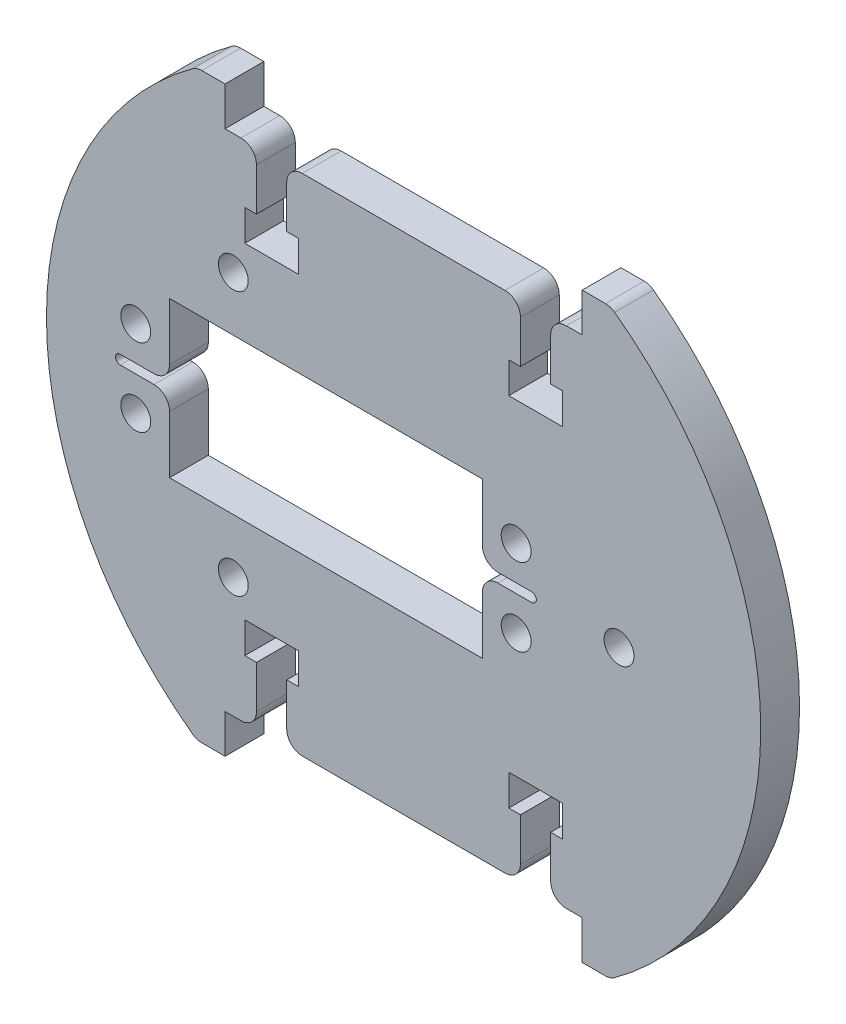
SolidWorks part; units mm, degrees
ref_plane "Plan de face" through (0, 0, 0) normal (0, 0, 1) x (1, 0, 0)
ref_plane "Plan de dessus" through (0, 0, 0) normal (0, 1, 0) x (1, 0, 0)
ref_plane "Plan de droite" through (0, 0, 0) normal (1, 0, 0) x (0, 0, -1)
sketch "Esquisse1" plane through (0, 0, 0) normal (0, 0, 1) x (1, 0, 0)
  line L0 (-21.9331, -17) -> (-21.9331, 17) construction
  line L1 (14.5, 5) -> (14.5, -5) construction
  line L2 (0, 0) -> (-21.9331, 0) construction
  line L3 (18.95, 30.5) -> (15.05, 30.5) construction
  line L4 (17, 21) -> (17, 30.5) construction
  line L5 (13.05, 32.5) -> (-13.05, 32.5)
  line L6 (15.05, 30.5) -> (15.05, 25)
  line L7 (15.05, 25) -> (13.55, 25)
  line L8 (13.55, 25) -> (13.55, 21)
  line L9 (26, -37.4976) -> (23, -37.5)
  line L10 (23, -37.5) -> (23, -32.5)
  line L11 (23, -32.5) -> (20.95, -32.5)
  line L12 (18.95, -25) -> (18.95, -30.5)
  line L13 (20.45, -25) -> (18.95, -25)
  line L14 (20.45, -21) -> (20.45, -25)
  line L15 (13.55, -21) -> (20.45, -21)
  line L16 (13.55, -25) -> (13.55, -21)
  line L17 (15.05, -25) -> (13.55, -25)
  line L18 (15.05, -30.5) -> (15.05, -25)
  line L19 (13.05, -32.5) -> (-13.05, -32.5)
  line L20 (17, -21) -> (17, -30.5) construction
  line L21 (18.95, -30.5) -> (15.05, -30.5) construction
  line L22 (0, 0) -> (46, 0) construction
  line L23 (13.55, 21) -> (20.45, 21)
  line L24 (20.45, 21) -> (20.45, 25)
  line L25 (20.45, 25) -> (18.95, 25)
  line L26 (18.95, 25) -> (18.95, 30.5)
  line L27 (23, 32.5) -> (20.95, 32.5)
  line L28 (23, 37.5) -> (23, 32.5)
  line L29 (26, 37.4976) -> (23, 37.5)
  line L30 (-18.95, -30.5) -> (-15.05, -30.5) construction
  line L31 (-17, -21) -> (-17, -30.5) construction
  line L32 (-15.05, -30.5) -> (-15.05, -25)
  line L33 (-15.05, -25) -> (-13.55, -25)
  line L34 (-13.55, -25) -> (-13.55, -21)
  line L35 (-13.55, -21) -> (-20.45, -21)
  line L36 (-20.45, -21) -> (-20.45, -25)
  line L37 (-20.45, -25) -> (-18.95, -25)
  line L38 (-18.95, -25) -> (-18.95, -30.5)
  line L39 (-23, -32.5) -> (-20.95, -32.5)
  line L40 (-23, -37.5) -> (-23, -32.5)
  line L41 (10.15, -10) -> (10.15, -2.6)
  line L42 (10.15, 2.6) -> (10.15, 10)
  line L43 (10.15, 10) -> (-30.15, 10)
  line L44 (-30.15, 10) -> (-30.15, 2.6)
  line L45 (-30.15, -2.6) -> (-30.15, -10)
  line L46 (-30.15, -10) -> (10.15, -10)
  line L47 (-26, -37.4976) -> (-23, -37.5)
  line L48 (-36.5, -0.6) -> (-32.15, -0.6)
  line L49 (12.15, -0.6) -> (16.5, -0.6)
  line L50 (-36.5, 0.6) -> (-32.15, 0.6)
  line L51 (12.15, 0.6) -> (16.5, 0.6)
  line L52 (-17, 21) -> (-17, 30.5) construction
  line L53 (-18.95, 30.5) -> (-15.05, 30.5) construction
  line L54 (-26, 37.4976) -> (-23, 37.5)
  line L55 (-23, 37.5) -> (-23, 32.5)
  line L56 (0, -32.5) -> (0, 32.5) construction
  line L57 (-23, 32.5) -> (-20.95, 32.5)
  line L58 (-18.95, 25) -> (-18.95, 30.5)
  line L59 (-20.45, 25) -> (-18.95, 25)
  line L60 (-20.45, 21) -> (-20.45, 25)
  line L61 (-13.55, 21) -> (-20.45, 21)
  line L62 (-13.55, 25) -> (-13.55, 21)
  line L63 (-15.05, 25) -> (-13.55, 25)
  line L64 (-15.05, 30.5) -> (-15.05, 25)
  circle A0 centre (27.75, 0) radius 1.925
  circle A1 centre (-21.9331, -17) radius 1.925
  circle A2 centre (-21.9331, 17) radius 1.925
  arc A3 (16.5, 0.6) -> (16.5, -0.6) centre (16.5, 0) cw
  arc A4 (27.1802, -37.1112) -> (27.1802, 37.1112) centre (0, 0) ccw
  arc A5 (-36.5, 0.6) -> (-36.5, -0.6) centre (-36.5, 0) ccw
  arc A6 (13.05, 32.5) -> (15.05, 30.5) centre (13.05, 30.5) cw
  arc A7 (26, -37.4976) -> (27.1802, -37.1112) centre (25.9984, -35.4976) ccw
  arc A8 (18.95, -30.5) -> (20.95, -32.5) centre (20.95, -30.5) ccw
  arc A9 (13.05, -32.5) -> (15.05, -30.5) centre (13.05, -30.5) ccw
  arc A10 (18.95, 30.5) -> (20.95, 32.5) centre (20.95, 30.5) cw
  arc A11 (26, 37.4976) -> (27.1802, 37.1112) centre (25.9984, 35.4976) cw
  arc A12 (-13.05, -32.5) -> (-15.05, -30.5) centre (-13.05, -30.5) cw
  arc A13 (-18.95, -30.5) -> (-20.95, -32.5) centre (-20.95, -30.5) cw
  arc A14 (-26, -37.4976) -> (-27.1802, -37.1112) centre (-25.9984, -35.4976) cw
  arc A15 (-27.1802, -37.1112) -> (-27.1802, 37.1112) centre (0, 0) cw
  arc A16 (-26, 37.4976) -> (-27.1802, 37.1112) centre (-25.9984, 35.4976) ccw
  arc A17 (-18.95, 30.5) -> (-20.95, 32.5) centre (-20.95, 30.5) ccw
  circle A18 centre (14.5, -5) radius 1.925
  circle A19 centre (14.5, 5) radius 1.925
  circle A20 centre (-34.5, -5) radius 1.925
  circle A21 centre (-34.5, 5) radius 1.925
  arc A22 (12.15, -0.6) -> (10.15, -2.6) centre (12.15, -2.6) ccw
  arc A23 (-13.05, 32.5) -> (-15.05, 30.5) centre (-13.05, 30.5) ccw
  arc A24 (-30.15, -2.6) -> (-32.15, -0.6) centre (-32.15, -2.6) ccw
  arc A27 (-32.15, 0.6) -> (-30.15, 2.6) centre (-32.15, 2.6) ccw
  arc A28 (10.15, 2.6) -> (12.15, 0.6) centre (12.15, 2.6) ccw
  dimension "D5" = 3.85
  dimension "D6" = 46
  dimension "D7" = 34
  dimension "D8" = 2
  dimension "D13" = 2
  dimension "D14" = 2
  dimension "D23" = 4.35
  dimension "D25" = 2
  dimension "D28" = 5
  dimension "D32" = 2
  dimension "D2" = 32.5
  dimension "D3" = 20
  dimension "D4" = 10
  dimension "D9" = 11.5
  dimension "D10" = 7.5
  dimension "D11" = 6.9
  dimension "D12" = 3.9
  dimension "D15" = 13.55
  dimension "D16" = 5.5
  dimension "D17" = 10.15
  dimension "D18" = 40.3
  dimension "D19" = 4.35
  dimension "D20" = 4.35
  dimension "D21" = 1.2
  dimension "D22" = 0.6
  dimension "D24" = 6.35
  dimension "D26" = 21.9331
  dimension "D27" = 10
  dimension "D29" = 10
  dimension "D30" = 4.35
  dimension "D31" = 6.35
  dimension "D33" = 27.75
  dimension "D34" = 2
  dimension "D35" = 5.2
  dimension "D36" = 2.6
  dimension "D37" = 5
  dimension "D38" = 6
  dimension "D39" = 3
extrude "Boss.-Extru.1" add sketch "Esquisse1" along normal blind 5
